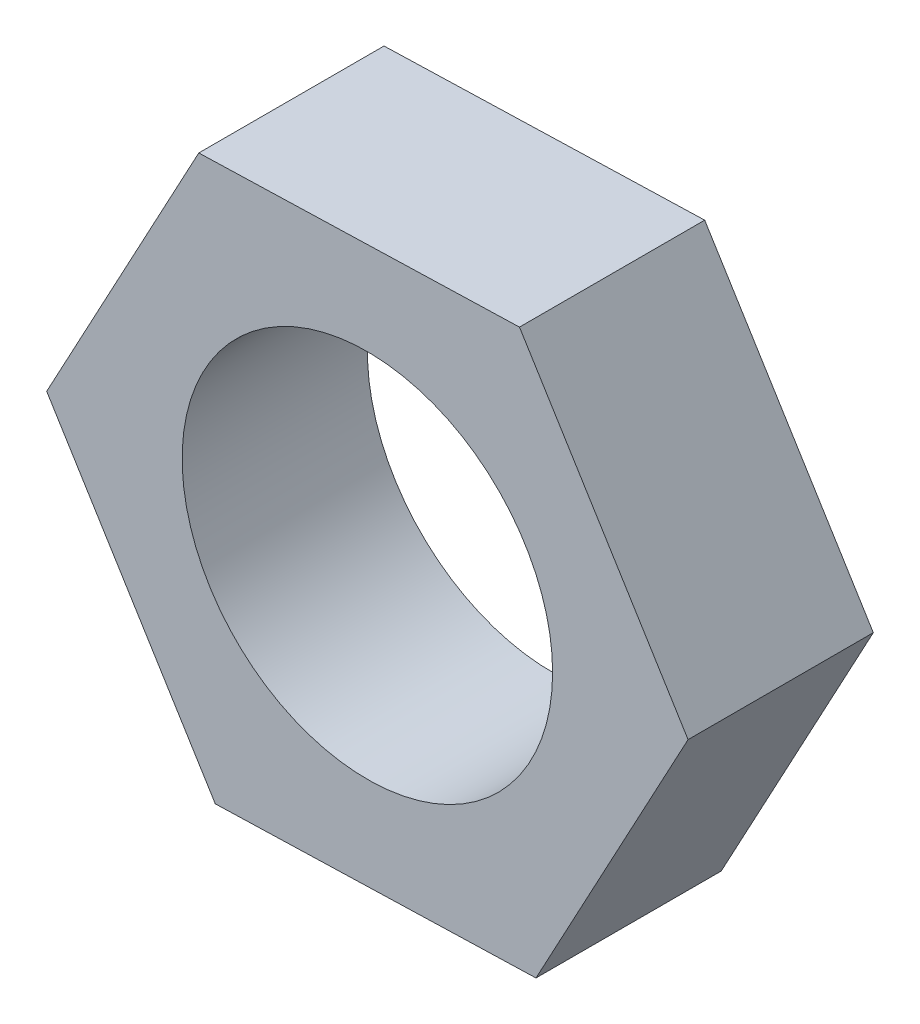
SolidWorks part; units mm, degrees
ref_plane "Front Plane" through (0, 0, 0) normal (0, 0, 1) x (1, 0, 0)
ref_plane "Top Plane" through (0, 0, 0) normal (0, 1, 0) x (1, 0, 0)
ref_plane "Right Plane" through (0, 0, 0) normal (1, 0, 0) x (0, 0, -1)
sketch "Sketch1" plane through (0, 0, 0) normal (0, 0, 1) x (1, 0, 0)
  line L1 (4.5509, -7.3681) -> (8.6564, 0.2571)
  line L2 (8.6564, 0.2571) -> (4.1055, 7.6253)
  line L3 (4.1055, 7.6253) -> (-4.5509, 7.3681)
  line L4 (-4.5509, 7.3681) -> (-8.6564, -0.2571)
  line L5 (-8.6564, -0.2571) -> (-4.1055, -7.6253)
  line L6 (-4.1055, -7.6253) -> (4.5509, -7.3681)
  circle A0 centre (0, 0) radius 5
  circle A2 centre (0, 0) radius 7.5 construction
  dimension "D1" = 15
  dimension "D2" = 10
extrude "Boss-Extrude2" add sketch "Sketch1" along normal blind 5
